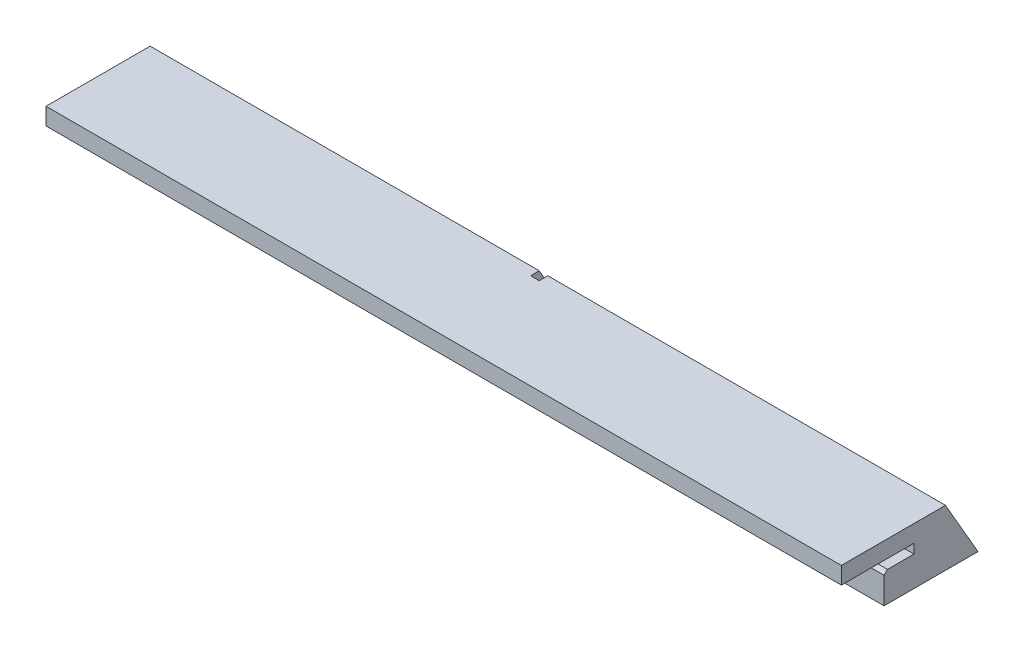
SolidWorks part; units mm, degrees
ref_plane "前视基准面" through (0, 0, 0) normal (0, 0, 1) x (1, 0, 0)
ref_plane "上视基准面" through (0, 0, 0) normal (0, 1, 0) x (1, 0, 0)
ref_plane "右视基准面" through (0, 0, 0) normal (1, 0, 0) x (0, 0, -1)
other "Configuration Table"
sketch "草图2" plane through (0, 0, 0) normal (0, 1, 0) x (1, 0, 0)
  line L1 (0, 0) -> (93.1, 0)
  line L2 (0, 0) -> (0, 10)
  line L3 (0, 10) -> (93.1, 10)
  line L4 (93.1, 0) -> (93.1, 10)
  dimension "D1" = 93.1
  dimension "D2" = 10
extrude "凸台-拉伸1" add sketch "草图2" along normal blind 3.5
sketch "草图4" plane through (0, 3.5, 0) normal (0, 1, 0) x (1, 0, 0)
  line L0 (93.1, 0) -> (93.1, 10) construction
  line L1 (0, 10) -> (93.1, 10)
  line L2 (0, 10) -> (0, 3.5)
  line L3 (0, 3.5) -> (93.1, 3.5)
  line L4 (93.1, 10) -> (93.1, 3.5)
  dimension "D1" = 6.5
extrude "凸台-拉伸2" add sketch "草图4" along normal blind 1.1
sketch "草图5" plane through (0, 4.6, 0) normal (0, 1, 0) x (1, 0, 0)
  line L0 (93.1, 3.5) -> (93.1, 10) construction
  line L1 (0, 10) -> (93.1, 10)
  line L2 (0, 10) -> (0, 0)
  line L3 (0, 0) -> (93.1, 0)
  line L4 (93.1, 10) -> (93.1, 0)
  dimension "D1" = 10
extrude "凸台-拉伸3" add sketch "草图5" along normal blind 2
sketch "草图6" plane through (0, 0, 0) normal (-1, 0, 0) x (0, 0, 1)
  line L0 (-10, 0) -> (-6.1895, 6.6)
  line L1 (-10, 0) -> (0, 0) construction
  line L2 (-10, 6.6) -> (-10, 0) construction
  line L3 (-10, 6.6) -> (0, 6.6) construction
  line L4 (-6.1895, 6.6) -> (-10, 6.6)
  line L5 (-10, 6.6) -> (-10, 0)
  dimension "D1" = 30
extrude "切除-拉伸1" cut sketch "草图6" against normal through all
sketch "草图7" plane through (0, 0, -3.5) normal (0, 0, 1) x (1, 0, 0)
  line L0 (0, 4.6) -> (93.1, 4.6) construction
  line L1 (5, 4.6) -> (88.1, 4.6)
  line L2 (5, 4.6) -> (5, 3.5)
  line L3 (5, 3.5) -> (88.1, 3.5)
  line L4 (88.1, 4.6) -> (88.1, 3.5)
  line L5 (0, 3.5) -> (93.1, 3.5) construction
  line L6 (0, 4.6) -> (0, 3.5) construction
  line L7 (93.1, 4.6) -> (93.1, 3.5) construction
  dimension "D1" = 5
  dimension "D2" = 5
extrude "凸台-拉伸4" add sketch "草图7" along normal up to surface (3.5 mm away) up to face at (46.55, 1.75, 0)
chamfer "倒角1" distance 0.4 angle 45 2 edges at (2.5, 3.5, 0) (90.6, 3.5, 0)
sketch "草图8" plane through (0, 0, 0) normal (0, -1, 0) x (1, 0, 0)
  line L0 (46.55, 147) -> (46.55, 0) construction
  line L1 (0, 0) -> (93.1, 0) construction
  line L2 (5, 0) -> (0, 0) construction
  circle A0 centre (46.55, 147) radius 150
  dimension "D1" = 300
  dimension "D2" = 147
extrude "切除-拉伸2" cut sketch "草图8" against normal up to next
sketch "草图9" plane through (0, 0, 0) normal (0, 0, 1) x (1, 0, 0)
  line L1 (0, 4.6) -> (93.1, 4.6)
  line L2 (0, 4.6) -> (0, 6.6)
  line L3 (0, 6.6) -> (93.1, 6.6)
  line L4 (93.1, 4.6) -> (93.1, 6.6)
extrude "凸台-拉伸5" add sketch "草图9" along normal blind 5 and the other way up to next
sketch "草图10" plane through (0, 4.3301, -7.5) normal (0, 0.5, -0.866) x (-1, 0, 0)
  line L4 (0, -5) -> (0, 2.621)
  line L5 (0, 2.621) -> (-93.1, 2.621)
  line L6 (-93.1, 2.621) -> (-93.1, -5)
  line L7 (-93.1, -5) -> (0, -5)
  line L8 (0, -5) -> (0, 2.621)
  line L9 (0, 2.621) -> (-93.1, 2.621)
  line L10 (-93.1, 2.621) -> (-93.1, -5)
  line L11 (-93.1, -5) -> (0, -5)
  dimension "D1" = 0
extrude "凸台-拉伸6" add sketch "草图10" along direction (0, 0, -1) on the side of the normal blind 1
sketch "草图11" plane through (0, 4.7631, -8.25) normal (0, 0.5, -0.866) x (-1, 0, 0)
  line L0 (0, 2.121) -> (-93.1, 2.121) construction
  line L1 (-46.55, 2.121) -> (-45.55, 2.121)
  line L2 (-46.55, 2.121) -> (-46.55, -5.5)
  line L3 (-46.55, -5.5) -> (-45.55, -5.5)
  line L4 (-45.55, 2.121) -> (-45.55, -5.5)
  line L5 (-93.1, -5.5) -> (0, -5.5) construction
  dimension "D1" = 1
extrude "切除-拉伸3" cut sketch "草图11" along direction (0, 0, 1) on the side against the normal blind 1
